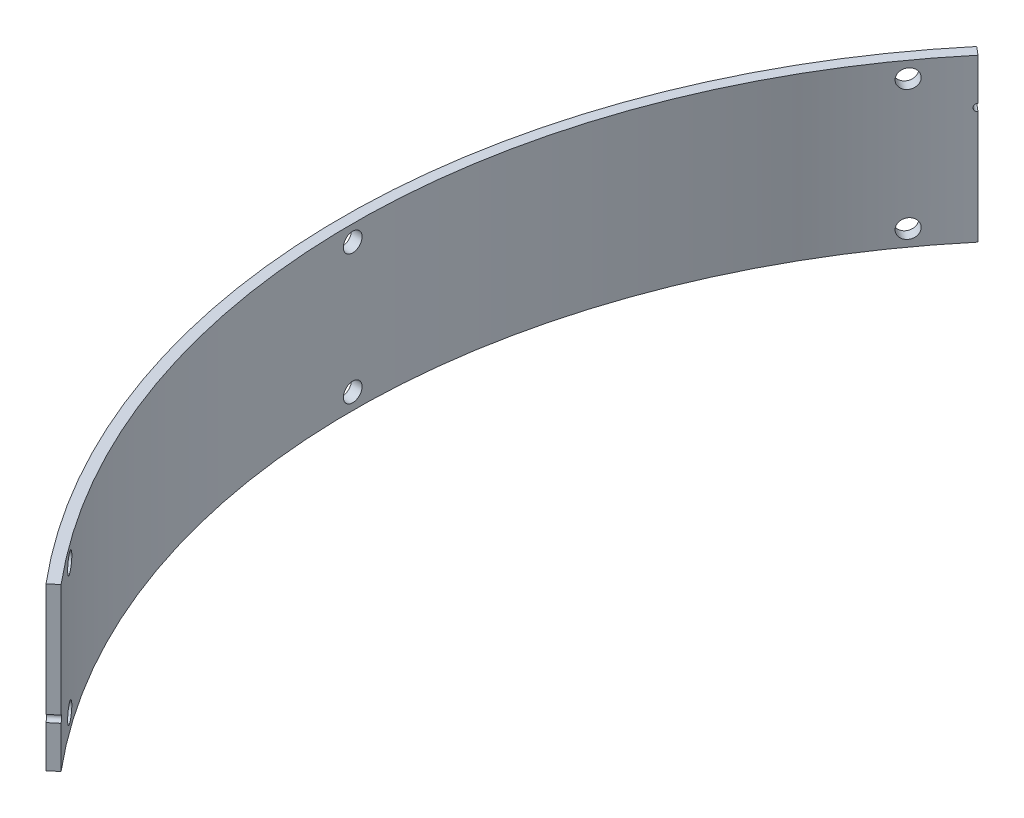
SolidWorks part; units mm, degrees
ref_plane "Front Plane" through (0, 0, 0) normal (0, 0, 1) x (1, 0, 0)
ref_plane "Top Plane" through (0, 0, 0) normal (0, 1, 0) x (1, 0, 0)
ref_plane "Right Plane" through (0, 0, 0) normal (1, 0, 0) x (0, 0, -1)
sketch "Sketch1" plane through (0, 0, 0) normal (0, 0, 1) x (1, 0, 0)
  line L0 (0, -1000) -> (0, 49000) construction
  line L1 (-101.5, 11.35) -> (-100, 11.35)
  line L2 (-101.5, 11.35) -> (-101.5, -11.35)
  line L3 (-101.5, -11.35) -> (-100, -11.35)
  line L4 (-100, 11.35) -> (-100, -11.35)
  line L5 (-101.5, 11.35) -> (-100, -11.35) construction
  line L6 (-101.5, -11.35) -> (-100, 11.35) construction
  point P0 (-100.75, 0)
  dimension "D1" = 1.5
  dimension "D2" = 22.7
  dimension "D3" = 100
revolve "Revolve1" add sketch "Sketch1" angle 80 mid plane about L0
sketch "Sketch2" plane through (0, 0, 0) normal (1, 0, 0) x (0, 0, -1)
  line L0 (0, -9.1) -> (0, 9.1) construction
  circle A0 centre (0, -9.1) radius 1.3125
  circle A1 centre (0, 9.1) radius 1.3125
  point P4 (0, 0)
  dimension "D1" = 2.625
  dimension "D2" = 18.2
extrude "Cut-Extrude1" cut sketch "Sketch2" against normal through all
pattern_circular "CirPattern1" count 2 every 36 about axis through (0, -1000, 0) along (0, 1, 0) of "Cut-Extrude1"
ref_plane "Plane1" through (-76.6044, 0, 64.2788) normal (0.766, 0, -0.6428) x (-0.6428, 0, -0.766)
sketch "Sketch3" plane through (-76.6044, 0, 64.2788) normal (0.766, 0, -0.6428) x (-0.6428, 0, -0.766)
  line L0 (0, -11.35) -> (0, 11.35) construction
  line L1 (0, -11.35) -> (98.4808, -11.35) construction
  circle A0 centre (0, -5) radius 0.5
  dimension "D1" = 1
  dimension "D2" = 6.35
extrude "Cut-Extrude2" cut sketch "Sketch3" against normal through all both and the other way through all
ref_plane "Plane2" through (-76.6044, 0, -64.2788) normal (-0.766, 0, -0.6428) x (-0.6428, 0, 0.766)
sketch "Sketch4" plane through (-76.6044, 0, -64.2788) normal (-0.766, 0, -0.6428) x (-0.6428, 0, 0.766)
  line L0 (0, -201000) -> (0, 249000) construction
  line L1 (98.4808, 11.35) -> (0, 11.35) construction
  circle A0 centre (0, 5) radius 0.5
  dimension "D1" = 1
  dimension "D2" = 6.35
extrude "Cut-Extrude3" cut sketch "Sketch4" against normal through all both and the other way through all
